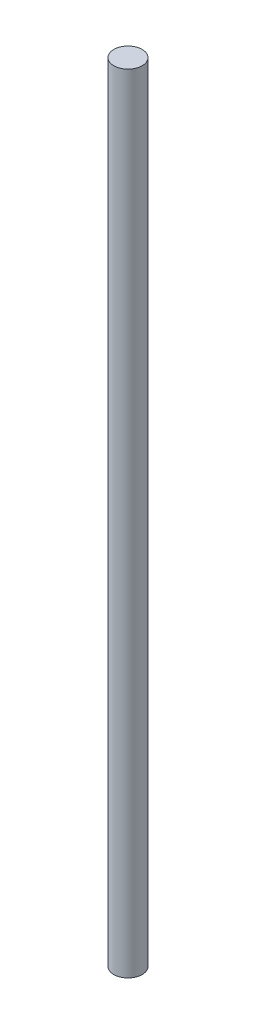
SolidWorks part; units mm, degrees
ref_plane "前视基准面" through (0, 0, 0) normal (0, 0, 1) x (1, 0, 0)
ref_plane "上视基准面" through (0, 0, 0) normal (0, 1, 0) x (1, 0, 0)
ref_plane "右视基准面" through (0, 0, 0) normal (1, 0, 0) x (0, 0, -1)
other "Configuration Table"
sketch "草图1" plane through (0, 0, 0) normal (0, 1, 0) x (1, 0, 0)
  circle A0 centre (0, 0) radius 9
  dimension "D1" = 18
extrude "凸台-拉伸1" add sketch "草图1" along normal mid plane 500
